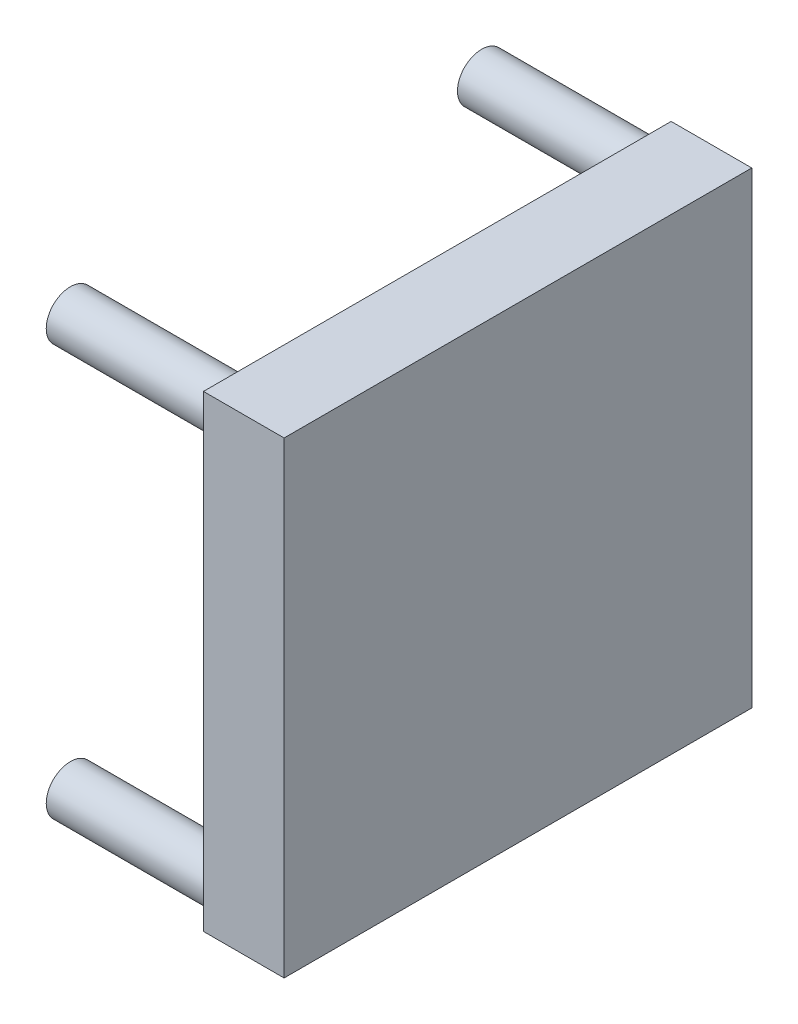
SolidWorks part; units mm, degrees
ref_plane "Front Plane" through (0, 0, 0) normal (0, 0, 1) x (1, 0, 0)
ref_plane "Top Plane" through (0, 0, 0) normal (0, 1, 0) x (1, 0, 0)
ref_plane "Right Plane" through (0, 0, 0) normal (1, 0, 0) x (0, 0, -1)
sketch "Sketch1" plane through (0, 0, 0) normal (1, 0, 0) x (0, 0, -1)
  line L1 (-14.5, -14.5) -> (14.5, -14.5)
  line L2 (-14.5, -14.5) -> (-14.5, 14.5)
  line L3 (-14.5, 14.5) -> (14.5, 14.5)
  line L4 (14.5, -14.5) -> (14.5, 14.5)
  line L5 (-14.5, -14.5) -> (14.5, 14.5) construction
  line L6 (-14.5, 14.5) -> (14.5, -14.5) construction
  point P0 (0, 0)
  dimension "D1" = 29
extrude "Boss-Extrude1" add sketch "Sketch1" along normal blind 5
sketch "Sketch2" plane through (0, 0, 0) normal (-1, 0, 0) x (0, 0, 1)
  line L1 (-12.75, -12.75) -> (12.75, -12.75) construction
  line L2 (-12.75, -12.75) -> (-12.75, 12.75) construction
  line L3 (-12.75, 12.75) -> (12.75, 12.75) construction
  line L4 (12.75, -12.75) -> (12.75, 12.75) construction
  line L5 (-12.75, -12.75) -> (12.75, 12.75) construction
  line L6 (-12.75, 12.75) -> (12.75, -12.75) construction
  circle A0 centre (-12.75, 12.75) radius 1.5
  circle A1 centre (12.75, 12.75) radius 1.5
  circle A2 centre (12.75, -12.75) radius 1.5
  circle A3 centre (-12.75, -12.75) radius 1.5
  point P0 (0, 0)
  dimension "D1" = 3
  dimension "D3" = 25.5
extrude "Boss-Extrude2" add sketch "Sketch2" along normal blind 10
